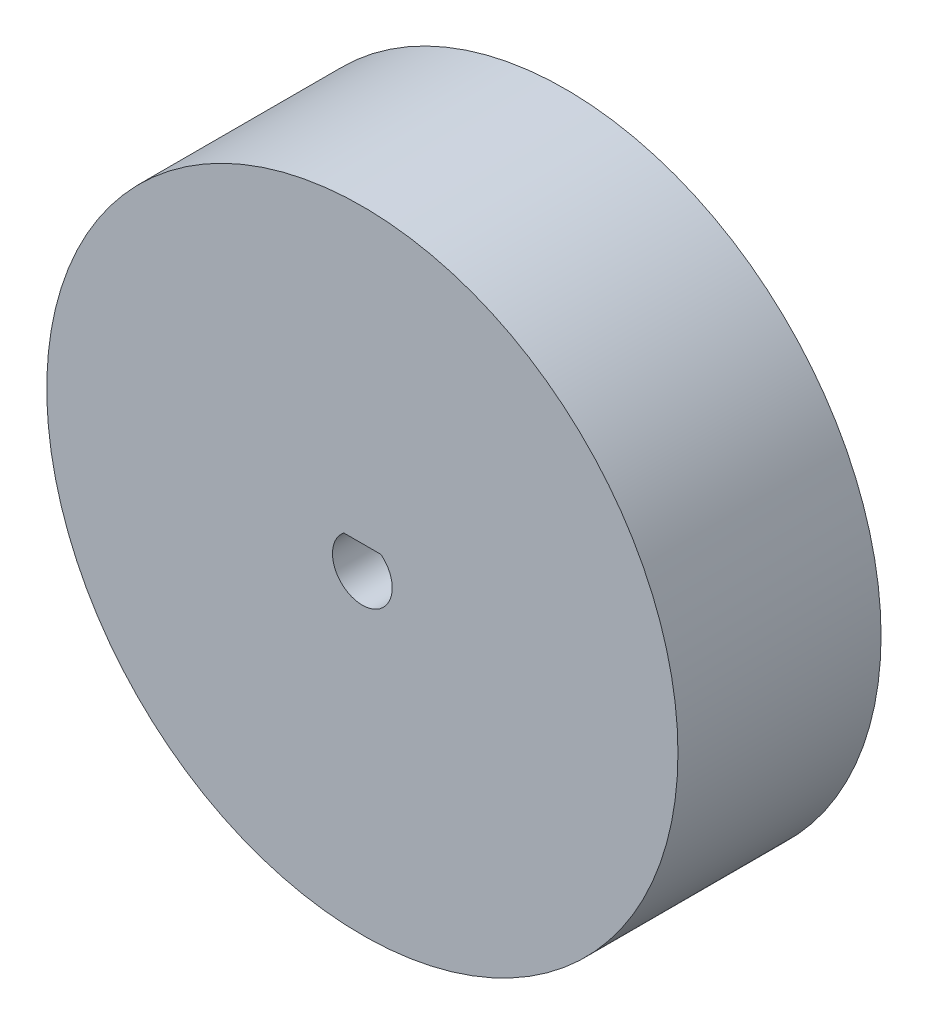
SolidWorks part; units mm, degrees
ref_plane "Front Plane" through (0, 0, 0) normal (0, 0, 1) x (1, 0, 0)
ref_plane "Top Plane" through (0, 0, 0) normal (0, 1, 0) x (1, 0, 0)
ref_plane "Right Plane" through (0, 0, 0) normal (1, 0, 0) x (0, 0, -1)
sketch "Sketch1" plane through (0, 0, 0) normal (0, 0, 1) x (1, 0, 0)
  line L0 (-1.27, 1.6025) -> (1.27, 1.6025)
  circle A0 centre (0, 0) radius 21.6
  arc A1 (-1.27, 1.6025) -> (1.27, 1.6025) centre (0, 0) ccw
  dimension "D1" = 4.0894
  dimension "D3" = 43.2
  dimension "D2" = 2.54
extrude "Boss-Extrude1" add sketch "Sketch1" along normal blind 13.9
sketch "Sketch2" plane through (0, 0, 0) normal (0, 0, -1) x (-1, 0, 0)
  circle A2 centre (0, 0) radius 26.68
  circle A3 centre (0, 0) radius 26.68
  circle A4 centre (0, 0) radius 21.6
  circle A5 centre (0, 0) radius 21.6
  dimension "D1" = 5.08
  dimension "D2" = 0
